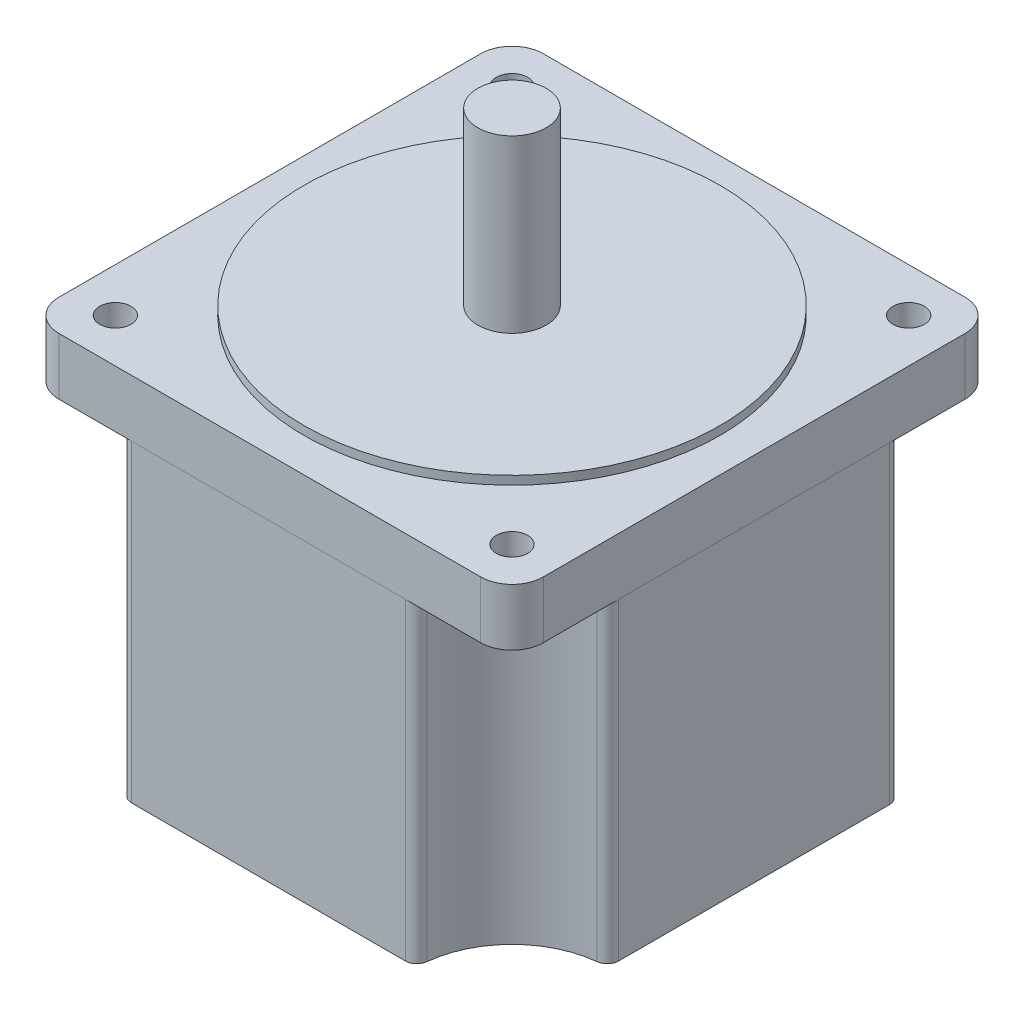
SolidWorks part; units mm, degrees
ref_plane "Спереди" through (0, 0, 0) normal (0, 0, 1) x (1, 0, 0)
ref_plane "Сверху" through (0, 0, 0) normal (0, 1, 0) x (1, 0, 0)
ref_plane "Справа" through (0, 0, 0) normal (1, 0, 0) x (0, 0, -1)
sketch "Эскиз1" plane through (0, 0, 0) normal (0, 1, 0) x (1, 0, 0)
  line L1 (-37, 42.5) -> (37, 42.5)
  line L2 (-42.5, 37) -> (-42.5, -37)
  line L3 (-37, -42.5) -> (37, -42.5)
  line L4 (42.5, 37) -> (42.5, -37)
  line L5 (-42.5, 42.5) -> (42.5, -42.5) construction
  line L6 (-42.5, -42.5) -> (42.5, 42.5) construction
  arc A0 (-42.5, 37) -> (-37, 42.5) centre (-37, 37) cw
  arc A1 (42.5, 37) -> (37, 42.5) centre (37, 37) ccw
  arc A2 (37, -42.5) -> (42.5, -37) centre (37, -37) ccw
  arc A3 (-42.5, -37) -> (-37, -42.5) centre (-37, -37) ccw
  circle A4 centre (-34.8, 34.8) radius 2.75
  circle A5 centre (34.8, 34.8) radius 2.75
  circle A6 centre (34.8, -34.8) radius 2.75
  circle A7 centre (-34.8, -34.8) radius 2.75
  point P0 (0, 0)
  dimension "D1" = 5.5
  dimension "D2" = 69.6
  dimension "D3" = 69.6
extrude "Вытянуть1" add sketch "Эскиз1" along normal blind 10
sketch "Эскиз2" plane through (0, 10, 0) normal (0, 1, 0) x (1, 0, 0)
  circle A0 centre (0, 0) radius 36.51
extrude "Вытянуть2" add sketch "Эскиз2" along normal blind 1.5
sketch "Эскиз3" plane through (0, 11.5, 0) normal (0, 1, 0) x (1, 0, 0)
  circle A0 centre (0, 0) radius 6
extrude "Вытянуть3" add sketch "Эскиз3" along normal blind 30
sketch "Эскиз4" plane through (0, 0, 0) normal (0, -1, 0) x (1, 0, 0)
  line L0 (42.5, 37) -> (42.5, -37) construction
  line L1 (30.5853, 30.5853) -> (44.1819, 16.9886) construction
  line L7 (0, 0) -> (70.0902, 0) construction
  line L8 (-42.7551, 23.9869) -> (-42.7551, -23.9869)
  line L9 (-24.2696, 42.4724) -> (23.7594, 42.4724)
  line L10 (42.4724, 23.7594) -> (42.4724, -23.7594)
  line L11 (23.7594, -42.4724) -> (-24.2696, -42.4724)
  arc A0 (-26.258, 40.6875) -> (-40.9703, 25.9753) centre (-42.7551, 42.4724) cw
  arc A1 (40.6875, -25.7478) -> (25.7478, -40.6875) centre (42.5, -42.5) ccw
  arc A2 (40.6875, 25.7478) -> (25.7478, 40.6875) centre (42.5, 42.5) cw
  arc A3 (-26.258, -40.6875) -> (-40.9703, -25.9753) centre (-42.7551, -42.4724) ccw
  arc A4 (-24.2696, -42.4724) -> (-26.258, -40.6875) centre (-24.2696, -40.4724) cw
  arc A5 (-40.9703, -25.9753) -> (-42.7551, -23.9869) centre (-40.7551, -23.9869) cw
  arc A6 (-40.9703, 25.9753) -> (-42.7551, 23.9869) centre (-40.7551, 23.9869) ccw
  arc A7 (-24.2696, 42.4724) -> (-26.258, 40.6875) centre (-24.2696, 40.4724) ccw
  arc A8 (25.7478, 40.6875) -> (23.7594, 42.4724) centre (23.7594, 40.4724) ccw
  arc A9 (42.4724, 23.7594) -> (40.6875, 25.7478) centre (40.4724, 23.7594) ccw
  arc A10 (40.6875, -25.7478) -> (42.4724, -23.7594) centre (40.4724, -23.7594) ccw
  arc A11 (23.7594, -42.4724) -> (25.7478, -40.6875) centre (23.7594, -40.4724) ccw
  point P19 (-26.1618, -42.4724)
  point P22 (-42.7551, -25.879)
  point P25 (-42.7551, 25.879)
  point P28 (-26.1618, 42.4724)
  point P31 (25.65, 42.4724)
  point P34 (42.4724, 25.65)
  point P37 (42.4724, -25.65)
  point P40 (25.65, -42.4724)
  point P41 (30.5853, 30.5853)
  dimension "D1" = 2
extrude "Вытянуть4" add sketch "Эскиз4" along normal blind 55
